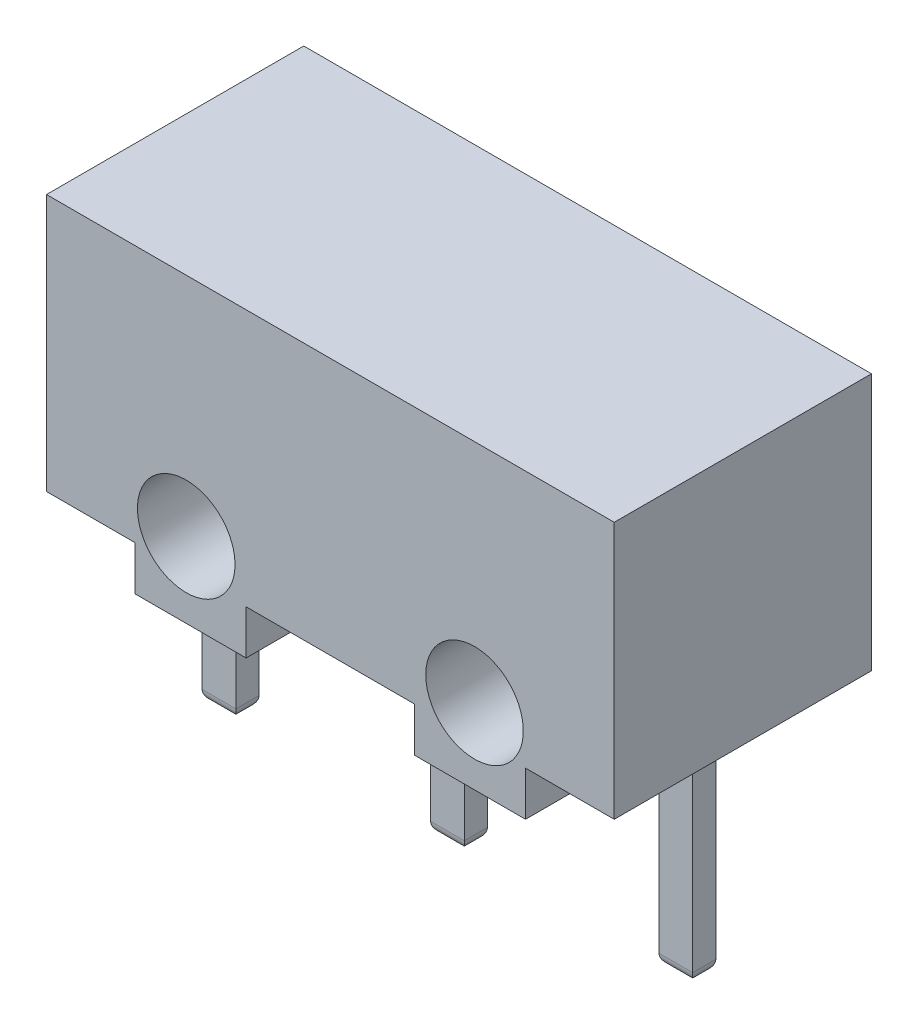
SolidWorks part; units mm, degrees
ref_plane "前视基准面" through (0, 0, 0) normal (0, 0, 1) x (1, 0, 0)
ref_plane "上视基准面" through (0, 0, 0) normal (0, 1, 0) x (1, 0, 0)
ref_plane "右视基准面" through (0, 0, 0) normal (1, 0, 0) x (0, 0, -1)
sketch "草图1" plane through (0, 0, 0) normal (0, 1, 0) x (1, 0, 0)
  line L1 (-6.4, -2.9) -> (6.4, -2.9)
  line L2 (-6.4, -2.9) -> (-6.4, 2.9)
  line L3 (-6.4, 2.9) -> (6.4, 2.9)
  line L4 (6.4, -2.9) -> (6.4, 2.9)
  line L5 (-6.4, -2.9) -> (6.4, 2.9) construction
  line L6 (-6.4, 2.9) -> (6.4, -2.9) construction
  point P0 (0, 0)
  dimension "D1" = 12.8
  dimension "D2" = 5.8
extrude "凸台-拉伸1" add sketch "草图1" along normal blind 5.8
sketch "草图2" plane through (0, 0, 0) normal (0, -1, 0) x (1, 0, 0)
  line L0 (0, 1.8263) -> (0, -1.8659) construction
  line L1 (-0.38, -0.26) -> (0.38, -0.26)
  line L2 (-0.38, -0.26) -> (-0.38, 0.26)
  line L3 (-0.38, 0.26) -> (0.38, 0.26)
  line L4 (0.38, -0.26) -> (0.38, 0.26)
  line L5 (-0.38, -0.26) -> (0.38, 0.26) construction
  line L6 (-0.38, 0.26) -> (0.38, -0.26) construction
  line L7 (0, 0) -> (-2.7691, 0) construction
  line L8 (4.77, -0.26) -> (4.77, 0.26)
  line L9 (4.77, -0.26) -> (5.53, -0.26)
  line L10 (5.53, -0.26) -> (5.53, 0.26)
  line L11 (4.77, 0.26) -> (5.53, 0.26)
  line L12 (-4.77, -0.26) -> (-5.53, -0.26)
  line L13 (-5.53, -0.26) -> (-5.53, 0.26)
  line L14 (-4.77, 0.26) -> (-5.53, 0.26)
  line L15 (-4.77, -0.26) -> (-4.77, 0.26)
  point P0 (0, 0)
  dimension "D1" = 0.76
  dimension "D2" = 0.52
  dimension "D3" = 2
extrude "凸台-拉伸2" add sketch "草图2" along normal blind 5
fillet "圆角3" radius 0.25 12 edges at (5.53, -5, 0) (5.15, -5, -0.26) (4.77, -5, 0) (5.15, -5, 0.26) (0, -5, -0.26) (-0.38, -5, 0) (0, -5, 0.26) (0.38, -5, 0) (-5.15, -5, -0.26) (-5.53, -5, 0) (-5.15, -5, 0.26) (-4.77, -5, 0)
sketch "草图4" plane through (0, 0, 0) normal (0, -1, 0) x (1, 0, 0)
  line L0 (-6.4, 2.9) -> (6.4, 2.9) construction
  line L1 (-4.4, 2.9) -> (-1.9, 2.9)
  line L2 (-4.4, 2.9) -> (-4.4, -2.9)
  line L3 (-4.4, -2.9) -> (-1.9, -2.9)
  line L4 (-1.9, 2.9) -> (-1.9, -2.9)
  line L5 (6.4, -2.9) -> (-6.4, -2.9) construction
  line L6 (0, 2.9) -> (0, -2.9) construction
  line L7 (-6.4, 2.9) -> (6.4, 2.9) construction
  line L8 (-6.4, -2.9) -> (-6.4, 2.9) construction
  line L9 (4.4, -2.9) -> (1.9, -2.9)
  line L10 (1.9, 2.9) -> (1.9, -2.9)
  line L11 (4.4, 2.9) -> (1.9, 2.9)
  line L12 (4.4, 2.9) -> (4.4, -2.9)
  dimension "D1" = 2
  dimension "D2" = 4.5
extrude "凸台-拉伸3" add sketch "草图4" along normal blind 1
sketch "草图3" plane through (0, 0, 2.9) normal (0, 0, 1) x (1, 0, 0)
  line L0 (0, 6.1089) -> (0, -0.6295) construction
  line L1 (-6.4, 5.8) -> (6.4, 5.8) construction
  circle A0 centre (-3.25, 0.7) radius 1.1
  circle A1 centre (3.25, 0.7) radius 1.1
  dimension "D1" = 6.5
  dimension "D2" = 5.1
  dimension "D3" = 2.2
extrude "切除-拉伸1" cut sketch "草图3" against normal through all
